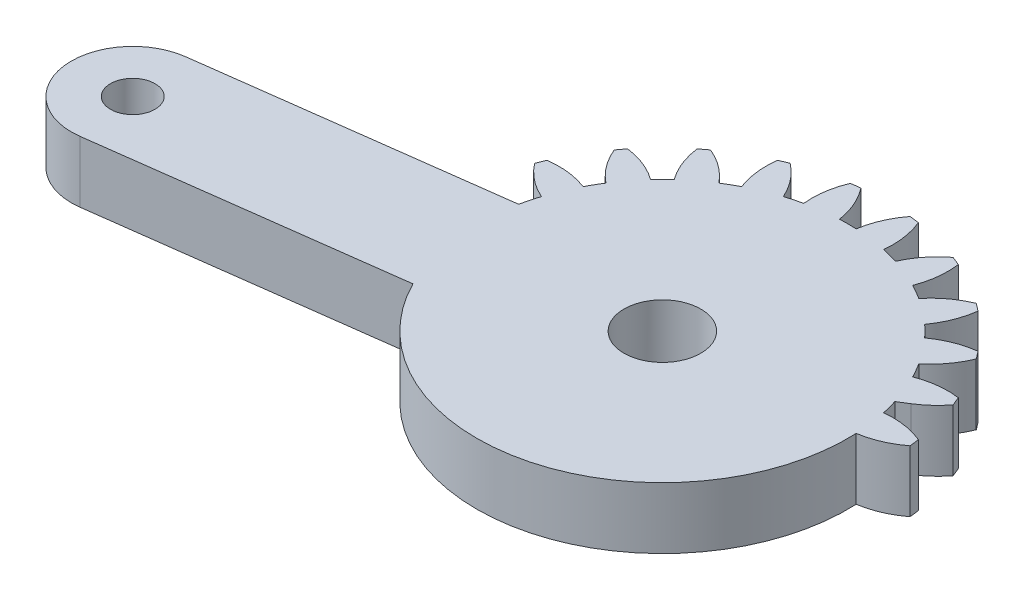
SolidWorks part; units mm, degrees
ref_plane "Front Plane" through (0, 0, 0) normal (0, 0, 1) x (1, 0, 0)
ref_plane "Top Plane" through (0, 0, 0) normal (0, 1, 0) x (1, 0, 0)
ref_plane "Right Plane" through (0, 0, 0) normal (1, 0, 0) x (0, 0, -1)
sketch "Sketch1" plane through (0, 0, 0) normal (0, 1, 0) x (1, 0, 0)
  line L0 (20.6437, 4) -> (2.0816, 4)
  line L1 (2.0816, -4) -> (20.6437, -4)
  arc A0 (2.0816, 4) -> (3.5217, 5.3071) centre (-0.7683, 8.5867) ccw
  arc A1 (3.5217, 5.3071) -> (3.2829, 5.8838) centre (-10.1063, 0) ccw
  arc A2 (3.2829, 5.8838) -> (0.6271, 5.5703) centre (2.5684, 0.5313) ccw
  arc A3 (0.6271, 5.5703) -> (0.0844, 6.5103) centre (-10.1063, 0) ccw
  arc A4 (0.0844, 6.5103) -> (1.6838, 8.6535) centre (-3.3089, 10.711) ccw
  arc A5 (1.6838, 8.6535) -> (1.3038, 9.1487) centre (-10.1063, 0) ccw
  arc A6 (1.3038, 9.1487) -> (-1.1803, 8.1585) centre (1.999, 3.7936) ccw
  arc A7 (-1.1803, 8.1585) -> (-1.9479, 8.926) centre (-10.1063, 0) ccw
  arc A8 (-1.9479, 8.926) -> (-0.9576, 11.4102) centre (-6.3127, 12.1053) ccw
  arc A9 (-0.9576, 11.4102) -> (-1.4528, 11.7901) centre (-10.1063, 0) ccw
  arc A10 (-1.4528, 11.7901) -> (-3.596, 10.1907) centre (0.6046, 6.7975) ccw
  arc A11 (-3.596, 10.1907) -> (-4.5361, 10.7334) centre (-10.1063, 0) ccw
  arc A12 (-4.5361, 10.7334) -> (-4.2225, 13.3892) centre (-9.5751, 12.6747) ccw
  arc A13 (-4.2225, 13.3892) -> (-4.7992, 13.6281) centre (-10.1063, 0) ccw
  arc A14 (-4.7992, 13.6281) -> (-6.4554, 11.5285) centre (-1.5196, 9.3381) ccw
  arc A15 (-6.4554, 11.5285) -> (-7.5039, 11.8094) centre (-10.1063, 0) ccw
  arc A16 (-7.5039, 11.8094) -> (-7.8884, 14.4558) centre (-12.8736, 12.3803) ccw
  arc A17 (-7.8884, 14.4558) -> (-8.5072, 14.5373) centre (-10.1063, 0) ccw
  arc A18 (-8.5072, 14.5373) -> (-9.5636, 12.0806) centre (-4.2291, 11.2423) ccw
  arc A19 (-9.5636, 12.0806) -> (-10.6491, 12.0806) centre (-10.1063, 0) ccw
  arc A20 (-10.6491, 12.0806) -> (-11.7054, 14.5373) centre (-15.9836, 11.2423) ccw
  arc A21 (-11.7054, 14.5373) -> (-12.3243, 14.4558) centre (-10.1063, 0) ccw
  arc A22 (-12.3243, 14.4558) -> (-12.7088, 11.8094) centre (-7.3391, 12.3803) ccw
  arc A23 (-12.7088, 11.8094) -> (-13.7573, 11.5285) centre (-10.1063, 0) ccw
  arc A24 (-13.7573, 11.5285) -> (-15.4135, 13.6281) centre (-18.6931, 9.3381) ccw
  arc A25 (-15.4135, 13.6281) -> (-15.9901, 13.3892) centre (-10.1063, 0) ccw
  arc A26 (-15.9901, 13.3892) -> (-15.6766, 10.7334) centre (-10.6376, 12.6747) ccw
  arc A27 (-15.6766, 10.7334) -> (-16.6166, 10.1907) centre (-10.1063, 0) ccw
  arc A28 (-16.6166, 10.1907) -> (-18.7599, 11.7901) centre (-20.8173, 6.7975) ccw
  arc A29 (-18.7599, 11.7901) -> (-19.255, 11.4102) centre (-10.1063, 0) ccw
  arc A30 (-19.255, 11.4102) -> (-18.2648, 8.926) centre (-13.9, 12.1053) ccw
  arc A31 (-18.2648, 8.926) -> (-19.0324, 8.1585) centre (-10.1063, 0) ccw
  arc A32 (-19.0324, 8.1585) -> (-21.5165, 9.1487) centre (-22.2117, 3.7936) ccw
  arc A33 (-21.5165, 9.1487) -> (-21.8965, 8.6535) centre (-10.1063, 0) ccw
  arc A34 (-21.8965, 8.6535) -> (-20.2971, 6.5103) centre (-16.9038, 10.711) ccw
  arc A35 (-20.2971, 6.5103) -> (-20.8398, 5.5703) centre (-10.1063, 0) ccw
  arc A36 (-20.8398, 5.5703) -> (-23.4956, 5.8838) centre (-22.7811, 0.5313) ccw
  arc A37 (-23.4956, 5.8838) -> (-23.7344, 5.3071) centre (-10.1063, 0) ccw
  arc A38 (-23.7344, 5.3071) -> (-21.6348, 3.6509) centre (-19.4444, 8.5867) ccw
  arc A39 (-21.6348, 3.6509) -> (-21.9157, 2.6025) centre (-10.1063, 0) ccw
  arc A40 (-21.9157, 2.6025) -> (-24.5622, 2.2179) centre (-22.4867, -2.7673) ccw
  arc A41 (-24.5622, 2.2179) -> (-24.6437, 1.5991) centre (-10.1063, 0) ccw
  arc A42 (-24.6437, 1.5991) -> (-22.1869, 0.5427) centre (-21.3486, 5.8773) ccw
  arc A43 (-22.1869, 0.5427) -> (-22.1869, -0.5427) centre (-10.1063, 0) ccw
  arc A44 (-22.1869, -0.5427) -> (-24.6437, -1.5991) centre (-21.3486, -5.8773) ccw
  arc A45 (-24.6437, -1.5991) -> (-24.5622, -2.2179) centre (-10.1063, 0) ccw
  arc A46 (-24.5622, -2.2179) -> (-21.9157, -2.6025) centre (-22.4867, 2.7673) ccw
  arc A47 (-21.9157, -2.6025) -> (-21.6348, -3.6509) centre (-10.1063, 0) ccw
  arc A48 (-21.6348, -3.6509) -> (-23.7344, -5.3071) centre (-19.4444, -8.5867) ccw
  arc A49 (-23.7344, -5.3071) -> (-23.4956, -5.8838) centre (-10.1063, 0) ccw
  arc A50 (-23.4956, -5.8838) -> (-20.8398, -5.5703) centre (-22.7811, -0.5313) ccw
  arc A51 (-20.8398, -5.5703) -> (-20.2971, -6.5103) centre (-10.1063, 0) ccw
  arc A52 (-20.2971, -6.5103) -> (-21.8965, -8.6535) centre (-16.9038, -10.711) ccw
  arc A53 (-21.8965, -8.6535) -> (-21.5165, -9.1487) centre (-10.1063, 0) ccw
  arc A54 (-21.5165, -9.1487) -> (-19.0324, -8.1585) centre (-22.2117, -3.7936) ccw
  arc A55 (-19.0324, -8.1585) -> (-18.2648, -8.926) centre (-10.1063, 0) ccw
  arc A56 (-18.2648, -8.926) -> (-19.255, -11.4102) centre (-13.9, -12.1053) ccw
  arc A57 (-19.255, -11.4102) -> (-18.7599, -11.7901) centre (-10.1063, 0) ccw
  arc A58 (-18.7599, -11.7901) -> (-16.6166, -10.1907) centre (-20.8173, -6.7975) ccw
  arc A59 (-16.6166, -10.1907) -> (-15.6766, -10.7334) centre (-10.1063, 0) ccw
  arc A60 (-15.6766, -10.7334) -> (-15.9901, -13.3892) centre (-10.6376, -12.6747) ccw
  arc A61 (-15.9901, -13.3892) -> (-15.4135, -13.6281) centre (-10.1063, 0) ccw
  arc A62 (-15.4135, -13.6281) -> (-13.7573, -11.5285) centre (-18.6931, -9.3381) ccw
  arc A63 (-13.7573, -11.5285) -> (-12.7088, -11.8094) centre (-10.1063, 0) ccw
  arc A64 (-12.7088, -11.8094) -> (-12.3243, -14.4558) centre (-7.3391, -12.3803) ccw
  arc A65 (-12.3243, -14.4558) -> (-11.7054, -14.5373) centre (-10.1063, 0) ccw
  arc A66 (-11.7054, -14.5373) -> (-10.6491, -12.0806) centre (-15.9836, -11.2423) ccw
  arc A67 (-10.6491, -12.0806) -> (-9.5636, -12.0806) centre (-10.1063, 0) ccw
  arc A68 (-9.5636, -12.0806) -> (-8.5072, -14.5373) centre (-4.2291, -11.2423) ccw
  arc A69 (-8.5072, -14.5373) -> (-7.8884, -14.4558) centre (-10.1063, 0) ccw
  arc A70 (-7.8884, -14.4558) -> (-7.5039, -11.8094) centre (-12.8736, -12.3803) ccw
  arc A71 (-7.5039, -11.8094) -> (-6.4554, -11.5285) centre (-10.1063, 0) ccw
  arc A72 (-6.4554, -11.5285) -> (-4.7992, -13.6281) centre (-1.5196, -9.3381) ccw
  arc A73 (-4.7992, -13.6281) -> (-4.2225, -13.3892) centre (-10.1063, 0) ccw
  arc A74 (-4.2225, -13.3892) -> (-4.5361, -10.7334) centre (-9.5751, -12.6747) ccw
  arc A75 (-4.5361, -10.7334) -> (-3.596, -10.1907) centre (-10.1063, 0) ccw
  arc A76 (-3.596, -10.1907) -> (-1.4528, -11.7901) centre (0.6046, -6.7975) ccw
  arc A77 (-1.4528, -11.7901) -> (-0.9576, -11.4102) centre (-10.1063, 0) ccw
  arc A78 (-0.9576, -11.4102) -> (-1.9479, -8.926) centre (-6.3127, -12.1053) ccw
  arc A79 (-1.9479, -8.926) -> (-1.1803, -8.1585) centre (-10.1063, 0) ccw
  arc A80 (-1.1803, -8.1585) -> (1.3038, -9.1487) centre (1.999, -3.7936) ccw
  arc A81 (1.3038, -9.1487) -> (1.6838, -8.6535) centre (-10.1063, 0) ccw
  arc A82 (1.6838, -8.6535) -> (0.0844, -6.5103) centre (-3.3089, -10.711) ccw
  arc A83 (0.0844, -6.5103) -> (0.6271, -5.5703) centre (-10.1063, 0) ccw
  arc A84 (0.6271, -5.5703) -> (3.2829, -5.8838) centre (2.5684, -0.5313) ccw
  arc A85 (3.2829, -5.8838) -> (3.5217, -5.3071) centre (-10.1063, 0) ccw
  arc A86 (3.5217, -5.3071) -> (2.0816, -4) centre (-0.7683, -8.5867) ccw
  arc A87 (20.6437, -4) -> (20.6437, 4) centre (20.6437, 0) ccw
  circle A88 centre (-10.1063, 0) radius 1.5
  circle A89 centre (20.6437, 0) radius 1.5
  dimension "D1" = 3
  dimension "D2" = 3
extrude "Boss-Extrude1" add sketch "Sketch1" along normal blind 4
sketch "Sketch3" plane through (0, 4, 0) normal (0, 1, 0) x (1, 0, 0)
  line L0 (-10.1063, 0) -> (-40.8563, 0) construction
  line L1 (-10.1063, 0) -> (-40.5933, -4.0137)
  line L2 (-10.6284, 3.9658) -> (-41.1154, -0.0479)
  line L3 (-9.5842, -3.9658) -> (-40.0712, -7.9795)
  line L4 (-10.1063, 0) -> (-4.5096, 13.5117) construction
  line L5 (-10.1063, 0) -> (-8.1974, 14.4999) construction
  circle A0 centre (-10.1063, 0) radius 1.5
  circle A1 centre (20.6437, 0) radius 1.5 construction
  circle A2 centre (20.6437, 0) radius 1.5
  circle A3 centre (-40.5933, -4.0137) radius 1.45
  circle A4 centre (-40.5933, -4.0137) radius 4
  circle A5 centre (-10.1063, 0) radius 4
  arc A6 (-4.2225, 13.3892) -> (-4.7992, 13.6281) centre (-10.1063, 0) ccw construction
  arc A7 (-7.8884, 14.4558) -> (-8.5072, 14.5373) centre (-10.1063, 0) ccw construction
  dimension "D2" = 3
  dimension "D5" = 2.9
  dimension "D6" = 8
  dimension "D7" = 8
  dimension "D1" = 30.75
  dimension "D4" = 7.5
extrude "Boss-Extrude2" add sketch "Sketch3" against normal blind 4
sketch "Sketch4" plane through (0, 4, 0) normal (0, 1, 0) x (1, 0, 0)
  line L0 (20.6437, 4) -> (2.0816, 4) construction
  line L1 (2.0816, -4) -> (20.6437, -4) construction
  line L2 (20.6437, 4) -> (2.0816, 4)
  line L3 (2.0816, -4) -> (20.6437, -4)
  line L4 (2.0816, 4) -> (1.4381, 3.6001)
  line L5 (-21.6245, -5.5509) -> (-20.8986, -5.4553)
  line L6 (-10.1063, 0) -> (0.0844, 6.5103) construction
  line L7 (-10.1063, 0) -> (1.9742, 0.5427) construction
  line L8 (-24.5755, 2.1296) -> (-41.1154, -0.0479)
  line L9 (-40.0712, -7.9795) -> (-23.5312, -5.8019)
  line L10 (2.0816, -4) -> (20.6437, -4)
  line L11 (20.6437, 4) -> (2.0816, 4)
  line L12 (-21.9429, 2.4762) -> (-41.1154, -0.0479)
  line L13 (-40.0712, -7.9795) -> (-21.6245, -5.5509)
  line L14 (2.0816, -4) -> (20.6437, -4)
  line L15 (20.6437, 4) -> (2.0816, 4)
  circle A0 centre (-10.1063, 0) radius 12.0927
  arc A1 (3.2829, 5.8838) -> (0.6271, 5.5703) centre (2.5684, 0.5313) ccw construction
  arc A2 (3.5217, 5.3071) -> (3.2829, 5.8838) centre (-10.1063, 0) ccw construction
  arc A3 (2.0816, 4) -> (3.5217, 5.3071) centre (-0.7683, 8.5867) ccw construction
  arc A4 (20.6437, -4) -> (20.6437, 4) centre (20.6437, 0) ccw construction
  arc A5 (3.5217, -5.3071) -> (2.0816, -4) centre (-0.7683, -8.5867) ccw construction
  arc A6 (3.2829, -5.8838) -> (3.5217, -5.3071) centre (-10.1063, 0) ccw construction
  arc A7 (0.6271, -5.5703) -> (3.2829, -5.8838) centre (2.5684, -0.5313) ccw construction
  arc A8 (3.2829, 5.8838) -> (0.6271, 5.5703) centre (2.5684, 0.5313) ccw
  arc A9 (3.5217, 5.3071) -> (3.2829, 5.8838) centre (-10.1063, 0) ccw
  arc A10 (2.0816, 4) -> (3.5217, 5.3071) centre (-0.7683, 8.5867) ccw
  arc A11 (20.6437, -4) -> (20.6437, 4) centre (20.6437, 0) ccw
  arc A12 (3.5217, -5.3071) -> (2.0816, -4) centre (-0.7683, -8.5867) ccw
  arc A13 (3.2829, -5.8838) -> (3.5217, -5.3071) centre (-10.1063, 0) ccw
  arc A14 (0.6271, -5.5703) -> (3.2829, -5.8838) centre (2.5684, -0.5313) ccw
  arc A15 (1.9742, 0.5427) -> (4.431, 1.5991) centre (1.1359, 5.8773) ccw
  arc A16 (4.3495, 2.2179) -> (1.7031, 2.6025) centre (2.274, -2.7673) ccw
  arc A17 (4.431, 1.5991) -> (4.3495, 2.2179) centre (-10.1063, 0) ccw
  arc A95 (-21.6348, 3.6509) -> (-21.9157, 2.6025) centre (-10.1063, 0) ccw
  arc A96 (-41.1154, -0.0479) -> (-40.0712, -7.9795) centre (-40.5933, -4.0137) ccw
  arc A97 (-20.2971, -6.5103) -> (-21.8965, -8.6535) centre (-16.9038, -10.711) ccw
  arc A98 (-21.8965, -8.6535) -> (-21.5165, -9.1487) centre (-10.1063, 0) ccw
  arc A99 (-21.5165, -9.1487) -> (-19.0324, -8.1585) centre (-22.2117, -3.7936) ccw
  arc A100 (-19.0324, -8.1585) -> (-18.2648, -8.926) centre (-10.1063, 0) ccw
  arc A101 (-18.2648, -8.926) -> (-19.255, -11.4102) centre (-13.9, -12.1053) ccw
  arc A102 (-19.255, -11.4102) -> (-18.7599, -11.7901) centre (-10.1063, 0) ccw
  arc A103 (-18.7599, -11.7901) -> (-16.6166, -10.1907) centre (-20.8173, -6.7975) ccw
  arc A104 (-16.6166, -10.1907) -> (-15.6766, -10.7334) centre (-10.1063, 0) ccw
  arc A105 (-15.6766, -10.7334) -> (-15.9901, -13.3892) centre (-10.6376, -12.6747) ccw
  arc A106 (-15.9901, -13.3892) -> (-15.4135, -13.6281) centre (-10.1063, 0) ccw
  arc A107 (-15.4135, -13.6281) -> (-13.7573, -11.5285) centre (-18.6931, -9.3381) ccw
  arc A108 (-13.7573, -11.5285) -> (-12.7088, -11.8094) centre (-10.1063, 0) ccw
  arc A109 (-12.7088, -11.8094) -> (-12.3243, -14.4558) centre (-7.3391, -12.3803) ccw
  arc A110 (-12.3243, -14.4558) -> (-11.7054, -14.5373) centre (-10.1063, 0) ccw
  arc A111 (-11.7054, -14.5373) -> (-10.6491, -12.0806) centre (-15.9836, -11.2423) ccw
  arc A112 (-10.6491, -12.0806) -> (-9.5636, -12.0806) centre (-10.1063, 0) ccw
  arc A113 (-9.5636, -12.0806) -> (-8.5072, -14.5373) centre (-4.2291, -11.2423) ccw
  arc A114 (-8.5072, -14.5373) -> (-7.8884, -14.4558) centre (-10.1063, 0) ccw
  arc A115 (-7.8884, -14.4558) -> (-7.5039, -11.8094) centre (-12.8736, -12.3803) ccw
  arc A116 (-7.5039, -11.8094) -> (-6.4554, -11.5285) centre (-10.1063, 0) ccw
  arc A117 (-6.4554, -11.5285) -> (-4.7992, -13.6281) centre (-1.5196, -9.3381) ccw
  arc A118 (-4.7992, -13.6281) -> (-4.2225, -13.3892) centre (-10.1063, 0) ccw
  arc A119 (-4.2225, -13.3892) -> (-4.5361, -10.7334) centre (-9.5751, -12.6747) ccw
  arc A120 (-4.5361, -10.7334) -> (-3.596, -10.1907) centre (-10.1063, 0) ccw
  arc A121 (-3.596, -10.1907) -> (-1.4528, -11.7901) centre (0.6046, -6.7975) ccw
  arc A122 (-1.4528, -11.7901) -> (-0.9576, -11.4102) centre (-10.1063, 0) ccw
  arc A123 (-0.9576, -11.4102) -> (-1.9479, -8.926) centre (-6.3127, -12.1053) ccw
  arc A124 (-1.9479, -8.926) -> (-1.1803, -8.1585) centre (-10.1063, 0) ccw
  arc A125 (-1.1803, -8.1585) -> (1.3038, -9.1487) centre (1.999, -3.7936) ccw
  arc A126 (1.3038, -9.1487) -> (1.6838, -8.6535) centre (-10.1063, 0) ccw
  arc A127 (1.6838, -8.6535) -> (0.0844, -6.5103) centre (-3.3089, -10.711) ccw
  arc A128 (0.0844, -6.5103) -> (0.6271, -5.5703) centre (-10.1063, 0) ccw
  arc A129 (0.6271, -5.5703) -> (3.2829, -5.8838) centre (2.5684, -0.5313) ccw
  arc A130 (3.2829, -5.8838) -> (3.5217, -5.3071) centre (-10.1063, 0) ccw
  arc A131 (3.5217, -5.3071) -> (2.0816, -4) centre (-0.7683, -8.5867) ccw
  arc A132 (20.6437, -4) -> (20.6437, 4) centre (20.6437, 0) ccw
  arc A133 (2.0816, 4) -> (3.5217, 5.3071) centre (-0.7683, 8.5867) ccw
  arc A134 (3.5217, 5.3071) -> (3.2829, 5.8838) centre (-10.1063, 0) ccw
  arc A135 (3.2829, 5.8838) -> (0.6271, 5.5703) centre (2.5684, 0.5313) ccw
  arc A136 (0.6271, 5.5703) -> (0.0844, 6.5103) centre (-10.1063, 0) ccw
  arc A137 (0.0844, 6.5103) -> (1.6838, 8.6535) centre (-3.3089, 10.711) ccw
  arc A138 (1.6838, 8.6535) -> (1.3038, 9.1487) centre (-10.1063, 0) ccw
  arc A139 (1.3038, 9.1487) -> (-1.1803, 8.1585) centre (1.999, 3.7936) ccw
  arc A140 (-1.1803, 8.1585) -> (-1.9479, 8.926) centre (-10.1063, 0) ccw
  arc A141 (-1.9479, 8.926) -> (-0.9576, 11.4102) centre (-6.3127, 12.1053) ccw
  arc A142 (-0.9576, 11.4102) -> (-1.4528, 11.7901) centre (-10.1063, 0) ccw
  arc A143 (-1.4528, 11.7901) -> (-3.596, 10.1907) centre (0.6046, 6.7975) ccw
  arc A144 (-3.596, 10.1907) -> (-4.5361, 10.7334) centre (-10.1063, 0) ccw
  arc A145 (-4.5361, 10.7334) -> (-4.2225, 13.3892) centre (-9.5751, 12.6747) ccw
  arc A146 (-4.2225, 13.3892) -> (-4.7992, 13.6281) centre (-10.1063, 0) ccw
  arc A147 (-4.7992, 13.6281) -> (-6.4554, 11.5285) centre (-1.5196, 9.3381) ccw
  arc A148 (-6.4554, 11.5285) -> (-7.5039, 11.8094) centre (-10.1063, 0) ccw
  arc A149 (-7.5039, 11.8094) -> (-7.8884, 14.4558) centre (-12.8736, 12.3803) ccw
  arc A150 (-7.8884, 14.4558) -> (-8.5072, 14.5373) centre (-10.1063, 0) ccw
  arc A151 (-8.5072, 14.5373) -> (-9.5636, 12.0806) centre (-4.2291, 11.2423) ccw
  arc A152 (-9.5636, 12.0806) -> (-10.6491, 12.0806) centre (-10.1063, 0) ccw
  arc A153 (-10.6491, 12.0806) -> (-11.7054, 14.5373) centre (-15.9836, 11.2423) ccw
  arc A154 (-11.7054, 14.5373) -> (-12.3243, 14.4558) centre (-10.1063, 0) ccw
  arc A155 (-12.3243, 14.4558) -> (-12.7088, 11.8094) centre (-7.3391, 12.3803) ccw
  arc A156 (-12.7088, 11.8094) -> (-13.7573, 11.5285) centre (-10.1063, 0) ccw
  arc A157 (-13.7573, 11.5285) -> (-15.4135, 13.6281) centre (-18.6931, 9.3381) ccw
  arc A158 (-15.4135, 13.6281) -> (-15.9901, 13.3892) centre (-10.1063, 0) ccw
  arc A159 (-15.9901, 13.3892) -> (-15.6766, 10.7334) centre (-10.6376, 12.6747) ccw
  arc A160 (-15.6766, 10.7334) -> (-16.6166, 10.1907) centre (-10.1063, 0) ccw
  arc A161 (-16.6166, 10.1907) -> (-18.7599, 11.7901) centre (-20.8173, 6.7975) ccw
  arc A162 (-18.7599, 11.7901) -> (-19.255, 11.4102) centre (-10.1063, 0) ccw
  arc A163 (-19.255, 11.4102) -> (-18.2648, 8.926) centre (-13.9, 12.1053) ccw
  arc A164 (-18.2648, 8.926) -> (-19.0324, 8.1585) centre (-10.1063, 0) ccw
  arc A165 (-19.0324, 8.1585) -> (-21.5165, 9.1487) centre (-22.2117, 3.7936) ccw
  arc A166 (-21.5165, 9.1487) -> (-21.8965, 8.6535) centre (-10.1063, 0) ccw
  arc A167 (-21.8965, 8.6535) -> (-20.2971, 6.5103) centre (-16.9038, 10.711) ccw
  arc A168 (-20.2971, 6.5103) -> (-20.8398, 5.5703) centre (-10.1063, 0) ccw
  arc A169 (-20.8398, 5.5703) -> (-23.4956, 5.8838) centre (-22.7811, 0.5313) ccw
  arc A170 (-23.4956, 5.8838) -> (-23.7344, 5.3071) centre (-10.1063, 0) ccw
  arc A171 (-23.7344, 5.3071) -> (-21.6348, 3.6509) centre (-19.4444, 8.5867) ccw
  arc A172 (-21.6348, 3.6509) -> (-21.9157, 2.6025) centre (-10.1063, 0) ccw
  arc A175 (-23.4956, -5.8838) -> (-20.8398, -5.5703) centre (-22.7811, -0.5313) ccw
  arc A176 (-41.1154, -0.0479) -> (-40.0712, -7.9795) centre (-40.5933, -4.0137) ccw
  arc A177 (-20.2971, -6.5103) -> (-21.8965, -8.6535) centre (-16.9038, -10.711) ccw
  arc A178 (-21.8965, -8.6535) -> (-21.5165, -9.1487) centre (-10.1063, 0) ccw
  arc A179 (-21.5165, -9.1487) -> (-19.0324, -8.1585) centre (-22.2117, -3.7936) ccw
  arc A180 (-19.0324, -8.1585) -> (-18.2648, -8.926) centre (-10.1063, 0) ccw
  arc A181 (-18.2648, -8.926) -> (-19.255, -11.4102) centre (-13.9, -12.1053) ccw
  arc A182 (-19.255, -11.4102) -> (-18.7599, -11.7901) centre (-10.1063, 0) ccw
  arc A183 (-18.7599, -11.7901) -> (-16.6166, -10.1907) centre (-20.8173, -6.7975) ccw
  arc A184 (-16.6166, -10.1907) -> (-15.6766, -10.7334) centre (-10.1063, 0) ccw
  arc A185 (-15.6766, -10.7334) -> (-15.9901, -13.3892) centre (-10.6376, -12.6747) ccw
  arc A186 (-15.9901, -13.3892) -> (-15.4135, -13.6281) centre (-10.1063, 0) ccw
  arc A187 (-15.4135, -13.6281) -> (-13.7573, -11.5285) centre (-18.6931, -9.3381) ccw
  arc A188 (-13.7573, -11.5285) -> (-12.7088, -11.8094) centre (-10.1063, 0) ccw
  arc A189 (-12.7088, -11.8094) -> (-12.3243, -14.4558) centre (-7.3391, -12.3803) ccw
  arc A190 (-12.3243, -14.4558) -> (-11.7054, -14.5373) centre (-10.1063, 0) ccw
  arc A191 (-11.7054, -14.5373) -> (-10.6491, -12.0806) centre (-15.9836, -11.2423) ccw
  arc A192 (-10.6491, -12.0806) -> (-9.5636, -12.0806) centre (-10.1063, 0) ccw
  arc A193 (-9.5636, -12.0806) -> (-8.5072, -14.5373) centre (-4.2291, -11.2423) ccw
  arc A194 (-8.5072, -14.5373) -> (-7.8884, -14.4558) centre (-10.1063, 0) ccw
  arc A195 (-7.8884, -14.4558) -> (-7.5039, -11.8094) centre (-12.8736, -12.3803) ccw
  arc A196 (-7.5039, -11.8094) -> (-6.4554, -11.5285) centre (-10.1063, 0) ccw
  arc A197 (-6.4554, -11.5285) -> (-4.7992, -13.6281) centre (-1.5196, -9.3381) ccw
  arc A198 (-4.7992, -13.6281) -> (-4.2225, -13.3892) centre (-10.1063, 0) ccw
  arc A199 (-4.2225, -13.3892) -> (-4.5361, -10.7334) centre (-9.5751, -12.6747) ccw
  arc A200 (-4.5361, -10.7334) -> (-3.596, -10.1907) centre (-10.1063, 0) ccw
  arc A201 (-3.596, -10.1907) -> (-1.4528, -11.7901) centre (0.6046, -6.7975) ccw
  arc A202 (-1.4528, -11.7901) -> (-0.9576, -11.4102) centre (-10.1063, 0) ccw
  arc A203 (-0.9576, -11.4102) -> (-1.9479, -8.926) centre (-6.3127, -12.1053) ccw
  arc A204 (-1.9479, -8.926) -> (-1.1803, -8.1585) centre (-10.1063, 0) ccw
  arc A205 (-1.1803, -8.1585) -> (1.3038, -9.1487) centre (1.999, -3.7936) ccw
  arc A206 (1.3038, -9.1487) -> (1.6838, -8.6535) centre (-10.1063, 0) ccw
  arc A207 (1.6838, -8.6535) -> (0.0844, -6.5103) centre (-3.3089, -10.711) ccw
  arc A208 (0.0844, -6.5103) -> (0.6271, -5.5703) centre (-10.1063, 0) ccw
  arc A209 (0.6271, -5.5703) -> (3.2829, -5.8838) centre (2.5684, -0.5313) ccw
  arc A210 (3.2829, -5.8838) -> (3.5217, -5.3071) centre (-10.1063, 0) ccw
  arc A211 (3.5217, -5.3071) -> (2.0816, -4) centre (-0.7683, -8.5867) ccw
  arc A212 (20.6437, -4) -> (20.6437, 4) centre (20.6437, 0) ccw
  arc A213 (2.0816, 4) -> (3.5217, 5.3071) centre (-0.7683, 8.5867) ccw
  arc A214 (3.5217, 5.3071) -> (3.2829, 5.8838) centre (-10.1063, 0) ccw
  arc A215 (3.2829, 5.8838) -> (0.6271, 5.5703) centre (2.5684, 0.5313) ccw
  arc A216 (0.6271, 5.5703) -> (0.0844, 6.5103) centre (-10.1063, 0) ccw
  arc A217 (0.0844, 6.5103) -> (1.6838, 8.6535) centre (-3.3089, 10.711) ccw
  arc A218 (1.6838, 8.6535) -> (1.3038, 9.1487) centre (-10.1063, 0) ccw
  arc A219 (1.3038, 9.1487) -> (-1.1803, 8.1585) centre (1.999, 3.7936) ccw
  arc A220 (-1.1803, 8.1585) -> (-1.9479, 8.926) centre (-10.1063, 0) ccw
  arc A221 (-1.9479, 8.926) -> (-0.9576, 11.4102) centre (-6.3127, 12.1053) ccw
  arc A222 (-0.9576, 11.4102) -> (-1.4528, 11.7901) centre (-10.1063, 0) ccw
  arc A223 (-1.4528, 11.7901) -> (-3.596, 10.1907) centre (0.6046, 6.7975) ccw
  arc A224 (-3.596, 10.1907) -> (-4.5361, 10.7334) centre (-10.1063, 0) ccw
  arc A225 (-4.5361, 10.7334) -> (-4.2225, 13.3892) centre (-9.5751, 12.6747) ccw
  arc A226 (-4.2225, 13.3892) -> (-4.7992, 13.6281) centre (-10.1063, 0) ccw
  arc A227 (-4.7992, 13.6281) -> (-6.4554, 11.5285) centre (-1.5196, 9.3381) ccw
  arc A228 (-6.4554, 11.5285) -> (-7.5039, 11.8094) centre (-10.1063, 0) ccw
  arc A229 (-7.5039, 11.8094) -> (-7.8884, 14.4558) centre (-12.8736, 12.3803) ccw
  arc A230 (-7.8884, 14.4558) -> (-8.5072, 14.5373) centre (-10.1063, 0) ccw
  arc A231 (-8.5072, 14.5373) -> (-9.5636, 12.0806) centre (-4.2291, 11.2423) ccw
  arc A232 (-9.5636, 12.0806) -> (-10.6491, 12.0806) centre (-10.1063, 0) ccw
  arc A233 (-10.6491, 12.0806) -> (-11.7054, 14.5373) centre (-15.9836, 11.2423) ccw
  arc A234 (-11.7054, 14.5373) -> (-12.3243, 14.4558) centre (-10.1063, 0) ccw
  arc A235 (-12.3243, 14.4558) -> (-12.7088, 11.8094) centre (-7.3391, 12.3803) ccw
  arc A236 (-12.7088, 11.8094) -> (-13.7573, 11.5285) centre (-10.1063, 0) ccw
  arc A237 (-13.7573, 11.5285) -> (-15.4135, 13.6281) centre (-18.6931, 9.3381) ccw
  arc A238 (-15.4135, 13.6281) -> (-15.9901, 13.3892) centre (-10.1063, 0) ccw
  arc A239 (-15.9901, 13.3892) -> (-15.6766, 10.7334) centre (-10.6376, 12.6747) ccw
  arc A240 (-15.6766, 10.7334) -> (-16.6166, 10.1907) centre (-10.1063, 0) ccw
  arc A241 (-16.6166, 10.1907) -> (-18.7599, 11.7901) centre (-20.8173, 6.7975) ccw
  arc A242 (-18.7599, 11.7901) -> (-19.255, 11.4102) centre (-10.1063, 0) ccw
  arc A243 (-19.255, 11.4102) -> (-18.2648, 8.926) centre (-13.9, 12.1053) ccw
  arc A244 (-18.2648, 8.926) -> (-19.0324, 8.1585) centre (-10.1063, 0) ccw
  arc A245 (-19.0324, 8.1585) -> (-21.5165, 9.1487) centre (-22.2117, 3.7936) ccw
  arc A246 (-21.5165, 9.1487) -> (-21.8965, 8.6535) centre (-10.1063, 0) ccw
  arc A247 (-21.8965, 8.6535) -> (-20.2971, 6.5103) centre (-16.9038, 10.711) ccw
  arc A248 (-20.2971, 6.5103) -> (-20.8398, 5.5703) centre (-10.1063, 0) ccw
  arc A249 (-20.8398, 5.5703) -> (-23.4956, 5.8838) centre (-22.7811, 0.5313) ccw
  arc A250 (-23.4956, 5.8838) -> (-23.7344, 5.3071) centre (-10.1063, 0) ccw
  arc A251 (-23.7344, 5.3071) -> (-21.6348, 3.6509) centre (-19.4444, 8.5867) ccw
  arc A252 (-23.4956, -5.8838) -> (-20.8398, -5.5703) centre (-22.7811, -0.5313) ccw
  arc A253 (-20.8398, -5.5703) -> (-20.2971, -6.5103) centre (-10.1063, 0) ccw
  arc A254 (-20.8398, -5.5703) -> (-20.2971, -6.5103) centre (-10.1063, 0) ccw
  arc A255 (-23.5312, -5.8019) -> (-23.4956, -5.8838) centre (-10.1063, 0) ccw
  arc A256 (-23.5312, -5.8019) -> (-23.4956, -5.8838) centre (-10.1063, 0) ccw
  arc A257 (-21.9157, 2.6025) -> (-24.5622, 2.2179) centre (-22.4867, -2.7673) ccw
  arc A258 (-21.9157, 2.6025) -> (-24.5622, 2.2179) centre (-22.4867, -2.7673) ccw
  arc A259 (-24.5622, 2.2179) -> (-24.5755, 2.1296) centre (-10.1063, 0) ccw
  arc A260 (-24.5622, 2.2179) -> (-24.5755, 2.1296) centre (-10.1063, 0) ccw
  point P40 (-10.1063, 0)
  dimension "D2" = 24.1855
  dimension "D4" = 30
  dimension "D1" = 0
  dimension "D3" = 2
extrude "Cut-Extrude1" cut sketch "Sketch4" against normal blind 4 contours A178 A179 A0 L5 A177 | A182 A183 A0 A181 | A186 A187 A0 A185 | A190 A191 A0 A189 | A194 A195 A0 A193 | A198 A199 A0 A197 | A202 A203 A0 A201 | A206 A207 A0 A205 | A258 A260 L12 A0 | L13 A256 A252 A0 L5 | A0 A14 A13 A12 L3 A11 L2 L4
sketch "Sketch5" plane through (0, 4, 0) normal (0, 1, 0) x (1, 0, 0)
  circle A0 centre (-10.1063, 0) radius 2.5
  circle A1 centre (-5.6063, 0) radius 1.3
  circle A2 centre (-14.6063, 0) radius 1.3
  circle A3 centre (-10.1063, 0) radius 1.5 construction
  dimension "D1" = 5
  dimension "D2" = 2.6
  dimension "D3" = 2.6
  dimension "D4" = 4.5
  dimension "D5" = 9
extrude "Cut-Extrude2" cut sketch "Sketch5" against normal up to next contours A0
sketch "Sketch6" plane through (0, 0, 0) normal (0, -1, 0) x (-1, 0, 0)
  circle A0 centre (10.1063, 0) radius 3.5
extrude "Boss-Extrude3" add sketch "Sketch6" along normal blind 1.5
sketch "Sketch7" plane through (0, -1.5, 0) normal (0, -1, 0) x (1, 0, 0)
  circle A0 centre (-10.1063, 0) radius 2.4941
extrude "Cut-Extrude3" cut sketch "Sketch7" against normal through all
